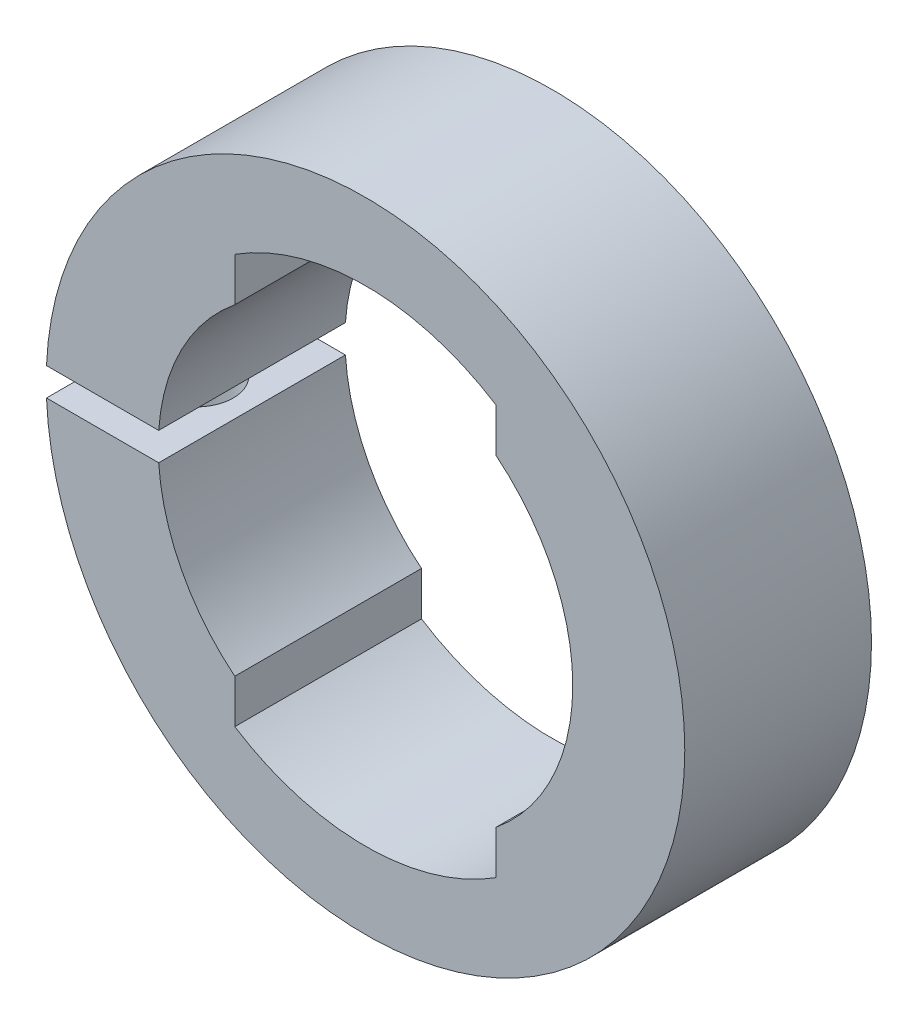
SolidWorks part; units mm, degrees
material "6061-T4 (SS)"
ref_plane "Front Plane" through (0, 0, 0) normal (0, 0, 1) x (1, 0, 0)
ref_plane "Top Plane" through (0, 0, 0) normal (0, 1, 0) x (1, 0, 0)
ref_plane "Right Plane" through (0, 0, 0) normal (1, 0, 0) x (0, 0, -1)
sketch "Sketch1" plane through (0, 0, 0) normal (0, 0, 1) x (1, 0, 0)
  line L0 (-7, 10.9545) -> (-7, 8.6145)
  line L1 (7, 10.9545) -> (7, 8.6145)
  line L2 (-7, -8.6145) -> (-7, -10.9545)
  line L3 (7, -8.6145) -> (7, -10.9545)
  line L4 (-17.0835, 0.75) -> (-11.0746, 0.75)
  line L5 (-17.0835, -0.75) -> (-11.0746, -0.75)
  line L6 (0, 0) -> (-7.7467, 0) construction
  arc A0 (-7, 8.6145) -> (-11.0746, 0.75) centre (0, 0) ccw
  arc A1 (-17.0835, -0.75) -> (-17.0835, 0.75) centre (0, 0) ccw
  arc A2 (-7, -10.9545) -> (7, -10.9545) centre (0, 0) ccw
  arc A3 (7, 10.9545) -> (-7, 10.9545) centre (0, 0) ccw
  circle A4 centre (0, 0) radius 11.1 construction
  arc A5 (7, -8.6145) -> (7, 8.6145) centre (0, 0) ccw
  circle A6 centre (0, 0) radius 17.1 construction
  arc A7 (-11.0746, -0.75) -> (-7, -8.6145) centre (0, 0) ccw
  dimension "D1" = 22.2
  dimension "D3" = 26
  dimension "D4" = 14
  dimension "D5" = 1.5
  dimension "D2" = 6
extrude "Boss-Extrude1" add sketch "Sketch1" along normal blind 10
sketch "Sketch2" plane through (0, -0.75, 0) normal (0, 1, 0) x (1, 0, 0)
  line L0 (-14.0791, 0) -> (-14.0791, -10) construction
  line L1 (-11.0746, 0) -> (-17.0835, 0) construction
  line L2 (-11.0746, -10) -> (-17.0835, -10) construction
  line L3 (-11.0746, -5) -> (-17.0835, -5) construction
  line L4 (-11.0746, -10) -> (-11.0746, 0) construction
  line L5 (-17.0835, -10) -> (-17.0835, 0) construction
  circle A0 centre (-14.0791, -5) radius 2
  point P14 (-13.5786, -5)
  point P15 (-13.5786, -5)
  dimension "D1" = 4
extrude "Cut-Extrude1" cut sketch "Sketch2" against normal through all both and the other way through all
